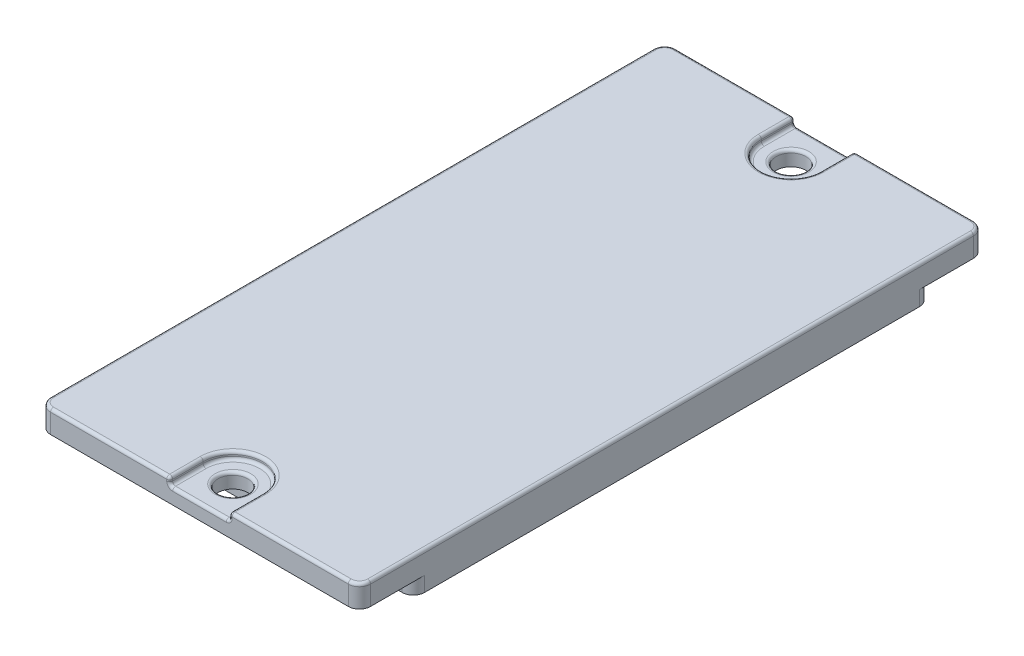
SolidWorks part; units mm, degrees
ref_plane "Front Plane" through (0, 0, 0) normal (0, 0, 1) x (1, 0, 0)
ref_plane "Top Plane" through (0, 0, 0) normal (0, 1, 0) x (1, 0, 0)
ref_plane "Right Plane" through (0, 0, 0) normal (1, 0, 0) x (0, 0, -1)
sketch "Sketch1" plane through (0, 0, 0) normal (0, 1, 0) x (1, 0, 0)
  line L0 (0, 0) -> (0, -37.5) construction
  line L1 (-21.5, 42) -> (21.5, 42)
  line L2 (-21.5, 42) -> (-21.5, -42)
  line L3 (-21.5, -42) -> (21.5, -42)
  line L4 (21.5, 42) -> (21.5, -42)
  line L5 (-21.5, 42) -> (21.5, -42) construction
  line L6 (-21.5, -42) -> (21.5, 42) construction
  line L7 (0, 0) -> (0, 37.5) construction
  circle A0 centre (0, 37.5) radius 2
  circle A1 centre (0, -37.5) radius 2
  point P0 (0, 0)
  dimension "D4" = 4
  dimension "D5" = 4
  dimension "D1" = 84
  dimension "D2" = 37.5
  dimension "D3" = 37.5
  dimension "D6" = 43
extrude "Boss-Extrude1" add sketch "Sketch1" along normal blind 3
sketch "Sketch2" plane through (0, 0, 0) normal (0, 1, 0) x (1, 0, 0)
  line L0 (21.5, -42) -> (21.5, 42) construction
  line L1 (-21.5, -34.75) -> (21.5, -34.75)
  line L2 (-21.5, -34.75) -> (-21.5, 34.75)
  line L3 (-21.5, 34.75) -> (21.5, 34.75)
  line L4 (21.5, -34.75) -> (21.5, 34.75)
  line L5 (-21.5, -34.75) -> (21.5, 34.75) construction
  line L6 (-21.5, 34.75) -> (21.5, -34.75) construction
  point P0 (0, 0)
  dimension "D1" = 69.5
extrude "Boss-Extrude2" add sketch "Sketch2" against normal blind 2
fillet "Fillet1" radius 1.5 8 edges at (21.5, 1.5, -42) (-21.5, 1.5, -42) (-21.5, 1.5, 42) (21.5, 1.5, 42) (21.5, -1, 34.75) (-21.5, -1, 34.75) (21.5, -1, -34.75) (-21.5, -1, -34.75)
sketch "Sketch3" plane through (0, 3, 0) normal (0, 1, 0) x (1, 0, 0)
  line L0 (-4, -37.5) -> (-4, -42)
  line L1 (-20, -42) -> (20, -42) construction
  line L2 (-4, -42) -> (4, -42)
  line L3 (4, -42) -> (4, -37.5)
  line L4 (-4, 37.5) -> (-4, 43.0854)
  line L5 (-4, 43.0854) -> (4, 43.0854)
  line L6 (4, 43.0854) -> (4, 37.5)
  arc A0 (-4, 37.5) -> (4, 37.5) centre (0, 37.5) ccw
  arc A1 (4, -37.5) -> (-4, -37.5) centre (0, -37.5) ccw
  dimension "D1" = 8
  dimension "D2" = 8
extrude "Cut-Extrude1" cut sketch "Sketch3" against normal offset from surface (1 mm away) 2 up to face at (0, 0, -35.5)
fillet "Fillet2" radius 0.4 30 edges at (0, 2, 42) (0, 2, -42) (-4, 2, 39.75) (4, 2, 39.75) (4, 2, -39.75) (-4, 2, -39.75) (4, 3, 39.75) (-4, 3, 39.75) (-4, 3, -39.75) (0, 3, -33.5) (12, 3, 42) (21.0607, 3, 41.5607) (21.5, 3, 0) (21.0607, 3, -41.5607) (-12, 3, 42) (-21.0607, 3, 41.5607) (-21.5, 3, 0) (-21.0607, 3, -41.5607) (0, 2, 39.5) (0, 2, 33.5) (0, 2, -35.5) (0, 2, -33.5) (4, 2.5, -42) (-4, 2.5, -42) (-4, 2.5, 42) (4, 2.5, 42) (0, 3, 33.5) (4, 3, -39.75) (12, 3, -42) (-12, 3, -42)
